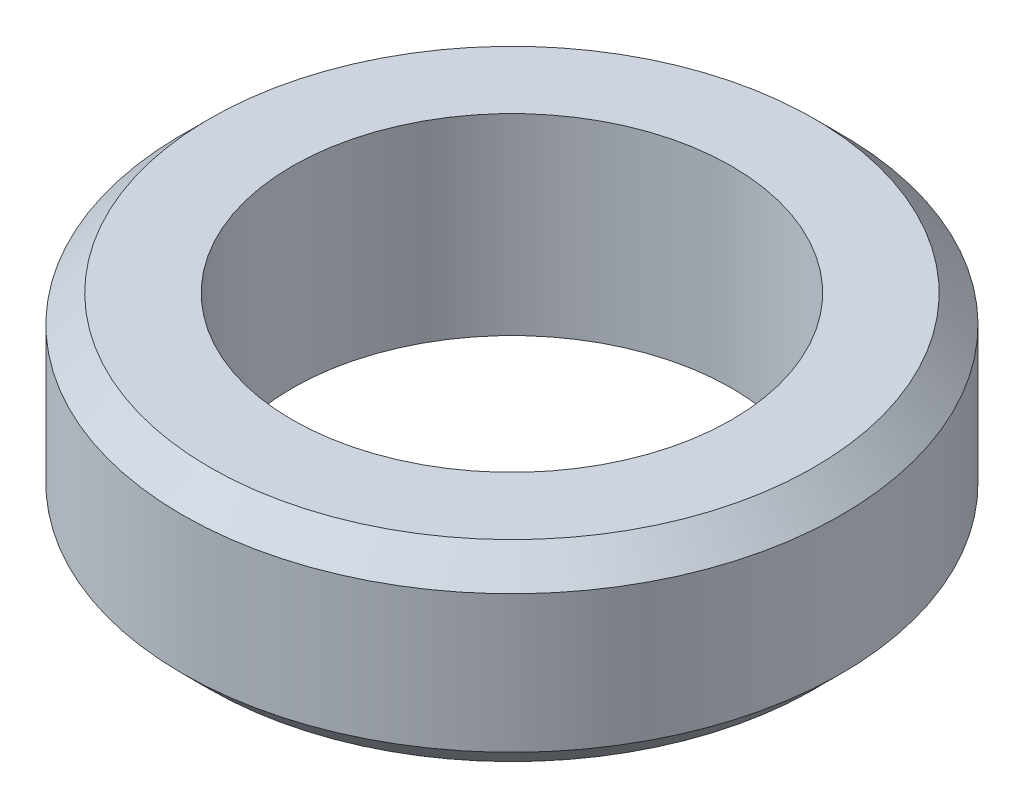
SolidWorks part; units mm, degrees
ref_plane "Front Plane" through (0, 0, 0) normal (0, 0, 1) x (1, 0, 0)
ref_plane "Top Plane" through (0, 0, 0) normal (0, 1, 0) x (1, 0, 0)
ref_plane "Right Plane" through (0, 0, 0) normal (1, 0, 0) x (0, 0, -1)
sketch "Sketch1" plane through (0, 0, 0) normal (0, 1, 0) x (1, 0, 0)
  circle A0 centre (0, 0) radius 4
  circle A1 centre (0, 0) radius 6
  dimension "D1" = 8
  dimension "D2" = 12
extrude "Boss-Extrude1" add sketch "Sketch1" along normal blind 3.5
chamfer "Chamfer1" distance 0.5 angle 45 2 edges at (0, 0, 6) (0, 3.5, 6)
